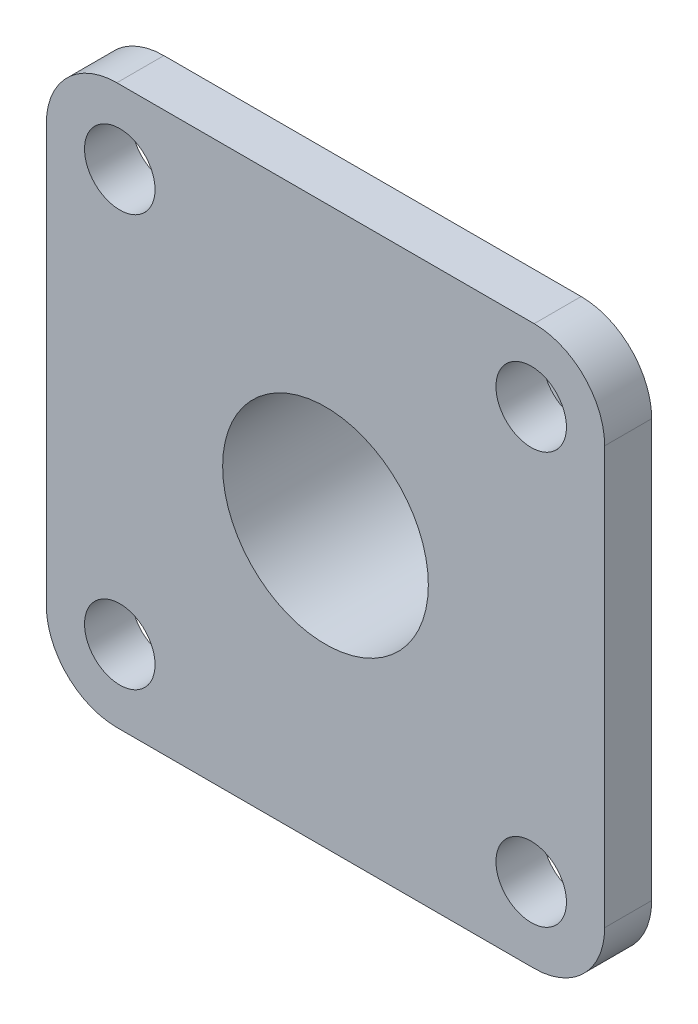
SolidWorks part; units mm, degrees
ref_plane "Front Plane" through (0, 0, 0) normal (0, 0, 1) x (1, 0, 0)
ref_plane "Top Plane" through (0, 0, 0) normal (0, 1, 0) x (1, 0, 0)
ref_plane "Right Plane" through (0, 0, 0) normal (1, 0, 0) x (0, 0, -1)
sketch "Sketch1" plane through (0, 0, 0) normal (0, 0, 1) x (-1, 0, 0)
  line L1 (-35.5, 47.5) -> (35.5, 47.5)
  line L2 (-47.5, 35.5) -> (-47.5, -35.5)
  line L3 (-35.5, -47.5) -> (35.5, -47.5)
  line L4 (47.5, 35.5) -> (47.5, -35.5)
  line L5 (-47.5, 47.5) -> (47.5, -47.5) construction
  line L6 (-47.5, -47.5) -> (47.5, 47.5) construction
  arc A0 (35.5, -47.5) -> (47.5, -35.5) centre (35.5, -35.5) ccw
  arc A1 (-47.5, -35.5) -> (-35.5, -47.5) centre (-35.5, -35.5) ccw
  arc A2 (-35.5, 47.5) -> (-47.5, 35.5) centre (-35.5, 35.5) ccw
  arc A3 (35.5, 47.5) -> (47.5, 35.5) centre (35.5, 35.5) cw
  circle A4 centre (35, 35) radius 6
  circle A5 centre (-35, 35) radius 6
  circle A7 centre (35, -35) radius 6
  circle A8 centre (-35, -35) radius 6
  circle A9 centre (0, 0) radius 17.5
  point P0 (0, 0)
  dimension "D2" = 12
  dimension "D3" = 35
  dimension "D1" = 95
extrude "Boss-Extrude1" add sketch "Sketch1" along normal blind 8
sketch "Sketch2" plane through (0, 0, 0) normal (0, 0, -1) x (-1, 0, 0)
  circle A0 centre (0, 0) radius 17.5
  circle A1 centre (0, 0) radius 27.5
  dimension "D2" = 35
  dimension "D1" = 10
extrude "Boss-Extrude2" add sketch "Sketch2" along normal blind 20
